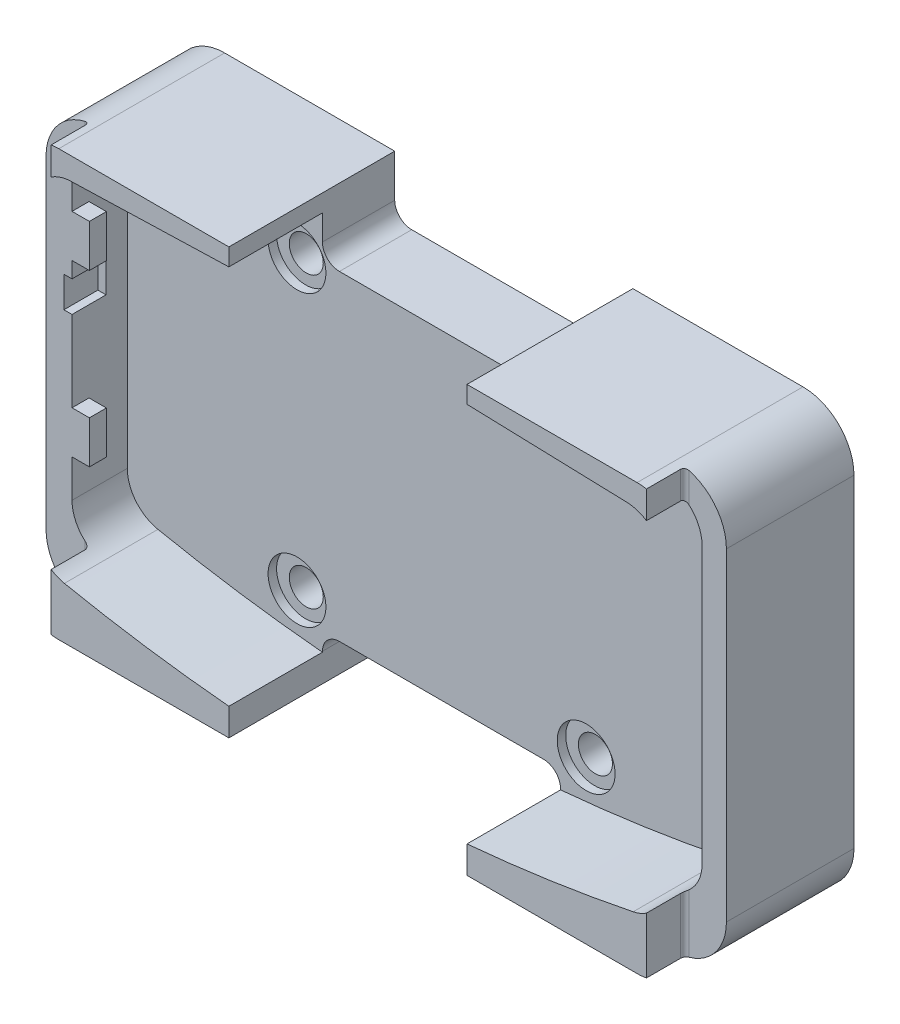
SolidWorks part; units mm, degrees
ref_plane "Front" through (0, 0, 0) normal (0, 0, 1) x (1, 0, 0)
ref_plane "Top" through (0, 0, 0) normal (0, 1, 0) x (1, 0, 0)
ref_plane "Right" through (0, 0, 0) normal (1, 0, 0) x (0, 0, -1)
sketch "XOR_Sketch1 (Mesh)_7" plane through (0, 0, 0) normal (0, 0, 1) x (1, 0, 0)
  line L0 (11.9012, 18.1042) -> (-12.0988, 18.1042)
  line L1 (39.9012, 19.1042) -> (39.9012, -18.8958)
  line L2 (33.9012, -24.8958) -> (13.9012, -24.8958)
  line L3 (-40.0988, -18.8958) -> (-40.0988, 19.1042)
  line L4 (-34.0988, 25.1042) -> (-14.0988, 25.1042)
  line L5 (-0.0988, 18.1042) -> (-0.0988, -37.0612) construction
  line L6 (-0.0988, 32.9388) -> (-0.0988, 25.1042) construction
  line L7 (-45.9, 0.1042) -> (57.25, 0.1042) construction
  line L8 (13.9012, -24.8958) -> (13.9012, -21.5708)
  line L9 (-14.0988, -21.5708) -> (-14.0988, -24.8958)
  line L10 (-14.0988, 20.1042) -> (-14.0988, 25.1042)
  line L11 (11.9012, -19.5708) -> (-12.0988, -19.5708)
  line L12 (13.9012, 25.1042) -> (33.9012, 25.1042)
  line L13 (-14.0988, -24.8958) -> (-34.0988, -24.8958)
  line L14 (13.9012, 25.1042) -> (13.9012, 20.1042)
  arc A0 (13.9012, -21.5708) -> (11.9012, -19.5708) centre (11.9012, -21.5708) ccw
  arc A1 (-34.0988, -24.8958) -> (-40.0988, -18.8958) centre (-34.0988, -18.8958) cw
  arc A2 (-12.0988, -19.5708) -> (-14.0988, -21.5708) centre (-12.0988, -21.5708) ccw
  arc A3 (-34.0988, 25.1042) -> (-40.0988, 19.1042) centre (-34.0988, 19.1042) ccw
  arc A4 (-14.0988, 20.1042) -> (-12.0988, 18.1042) centre (-12.0988, 20.1042) ccw
  arc A5 (33.9012, 25.1042) -> (39.9012, 19.1042) centre (33.9012, 19.1042) cw
  arc A6 (11.9012, 18.1042) -> (13.9012, 20.1042) centre (11.9012, 20.1042) ccw
  arc A7 (33.9012, -24.8958) -> (39.9012, -18.8958) centre (33.9012, -18.8958) ccw
  dimension "D2" = 2
  dimension "D6" = 2
  dimension "D8" = 2
  dimension "D14" = 6
  dimension "D15" = 2
  dimension "D1" = 50
  dimension "D3" = 5.325
  dimension "D4" = 25
  dimension "D5" = 28
  dimension "D7" = 14
  dimension "D9" = 28
  dimension "D10" = 40
  dimension "D11" = 7
  dimension "D12" = 14
  dimension "D13" = 80
extrude "XOR_Extrude1_580" add sketch "XOR_Sketch1 (Mesh)_7" along normal blind 11 and the other way blind 8.5 separate body
sketch "XOR_Sketch2 (Mesh)_581" plane through (0, 0, 0) normal (0, 0, 1) x (1, 0, 0)
  line L0 (-45, 0) -> (47.95, 0) construction
  line L1 (0, 33.1487) -> (0, -34.0513) construction
  line L2 (37.0426, 18.0021) -> (37.0426, -14.4202)
  line L3 (32.6802, 22.5) -> (0, 23.5)
  line L4 (-32.6802, 22.5) -> (0, 23.5)
  line L5 (-37.0426, 18.0021) -> (-37.0426, -14.4202)
  arc A0 (-37.0426, -14.4202) -> (-33.44, -18.8298) centre (-32.5426, -14.4202) ccw
  arc A1 (-37.0426, 18.0021) -> (-32.6802, 22.5) centre (-32.5426, 18.0021) cw
  arc A2 (37.0426, -14.4202) -> (33.44, -18.8298) centre (32.5426, -14.4202) cw
  arc A3 (37.0426, 18.0021) -> (32.6802, 22.5) centre (32.5426, 18.0021) ccw
  arc A4 (33.44, -18.8298) -> (0, -22.3936) centre (-2.0586, 155.5945) cw
  arc A5 (-33.44, -18.8298) -> (0, -22.3936) centre (2.0586, 155.5945) ccw
  dimension "D1" = 178
  dimension "D3" = 4.5
  dimension "D4" = 4.5
  dimension "D2" = 74.0852
  dimension "D5" = 23.5
  dimension "D6" = 22.5
extrude "XOR_Extrude2 (Cut)_582" cut sketch "XOR_Sketch2 (Mesh)_581" along normal blind 23
sketch "XOR_Sketch3 (Mesh)_583" plane through (0, 0, 0) normal (0, 1, 0) x (1, 0, 0)
  line L0 (35, -7) -> (35, -20.6801)
  line L1 (35, -20.6801) -> (45.656, -20.6801)
  line L2 (45.656, -20.6801) -> (45.656, -6.5)
  line L3 (0, 18.55) -> (0, -30.9) construction
  line L4 (-45.656, -20.6801) -> (-45.656, -6.5)
  line L5 (-45.656, -6.5) -> (-35.5, -6.5)
  line L6 (-35, -7) -> (-35, -20.6801)
  line L7 (45.656, -6.5) -> (35.5, -6.5)
  line L8 (-35, -20.6801) -> (-45.656, -20.6801)
  arc A0 (-35, -7) -> (-35.5, -6.5) centre (-35.5, -7) ccw
  arc A1 (35.5, -6.5) -> (35, -7) centre (35.5, -7) ccw
  dimension "D1" = 0.5
  dimension "D2" = 0.5
extrude "XOR_Extrude3 (Cut)_585" cut sketch "XOR_Sketch3 (Mesh)_583" along normal blind 30 and the other way blind 31.5
sketch "XOR_Sketch4 (Mesh)_586" plane through (0, 0, 0) normal (0, 0, 1) x (1, 0, 0)
  line L0 (-47.65, 0) -> (56, 0) construction
  line L1 (0, 41.75) -> (0, -41.35) construction
  circle A0 centre (-17, -17) radius 2
  circle A1 centre (-17, 17) radius 2
  circle A2 centre (17, -17) radius 2
  circle A3 centre (17, 17) radius 2
  dimension "D3" = 4
  dimension "D1" = 34
  dimension "D2" = 34
extrude "XOR_Extrude4 (Cut)_587" cut sketch "XOR_Sketch4 (Mesh)_586" against normal blind 30
sketch "XOR_Sketch5 (Mesh)_588" plane through (0, 0, 0) normal (0, 0, 1) x (1, 0, 0)
  line L0 (-0.0892, 26.1) -> (-0.0892, -31.4) construction
  line L1 (-44.35, 0.1436) -> (47.45, 0.1436) construction
  circle A0 centre (16.9108, 17.1436) radius 3.4
  circle A1 centre (-17.0892, 17.1436) radius 3.4
  circle A2 centre (16.9108, -16.8564) radius 3.4
  circle A3 centre (-17.0892, -16.8564) radius 3.4
  dimension "D3" = 6.8
  dimension "D1" = 34
  dimension "D2" = 34
extrude "XOR_Extrude5 (Cut)_949" cut sketch "XOR_Sketch5 (Mesh)_588" against normal blind 1
ref_plane "XOR_Plane1_1576" through (0, 0, 6.5) normal (0, 0, 1) x (1, 0, 0)
sketch "XOR_Sketch6 (Mesh)_1066" plane through (0, 0, 6.5) normal (0, 0, 1) x (1, 0, 0)
  line L0 (-35, -5) -> (-38.25, -5)
  line L1 (-37.9, 15) -> (-37.9, 10)
  line L2 (-37.9, 10) -> (-35, 10)
  line L3 (-38.25, -5) -> (-38.25, -10)
  line L4 (-35, 10) -> (-35, 15)
  line L5 (-38.25, -10) -> (-35, -10)
  line L6 (-35, 15) -> (-37.9, 15)
  line L7 (-35, -10) -> (-35, -5)
  dimension "D1" = 15
  dimension "D2" = 5
  dimension "D3" = 5
extrude "XOR_Extrude6 (Merge)_1279" add sketch "XOR_Sketch6 (Mesh)_1066" against normal blind 2
sketch "XOR_Sketch7 (Mesh)_2256" plane through (0, 0, 6.5) normal (0, 0, 1) x (1, 0, 0)
  line L0 (-35, 8.1235) -> (-35, 4.5)
  line L1 (-35, 4.5) -> (-38, 4.5)
  line L2 (-38, 4.5) -> (-38, 8.1235)
  line L3 (-38, 8.1235) -> (-35, 8.1235)
extrude "XOR_Extrude7 (Cut)_2327" cut sketch "XOR_Sketch7 (Mesh)_2256" against normal blind 4
